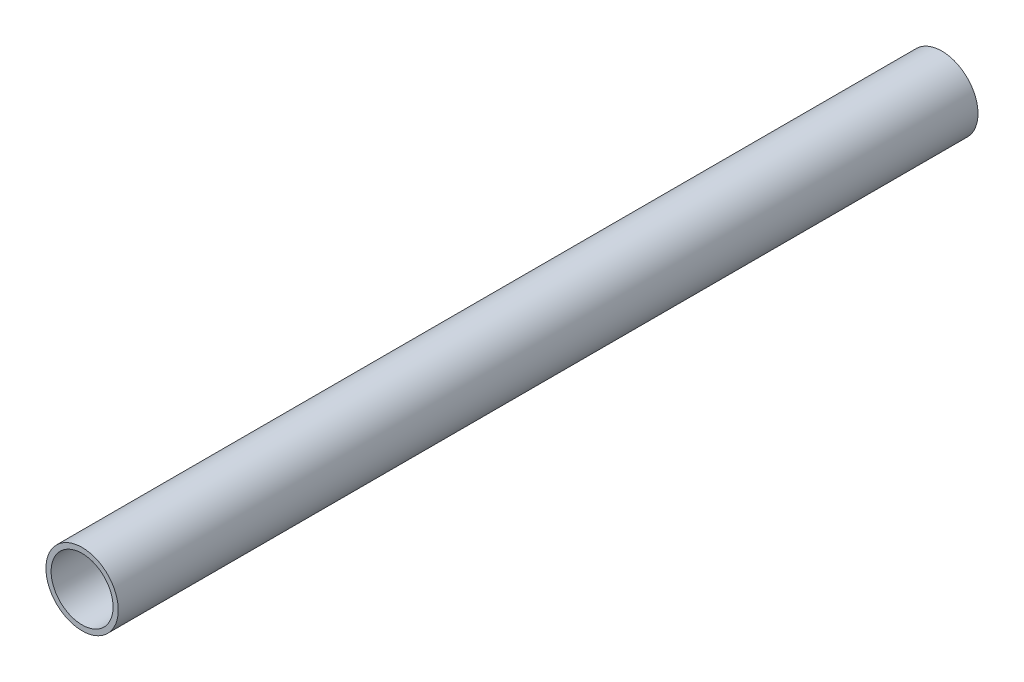
SolidWorks part; units mm, degrees
material "Thornel VCB-20 Carbon Cloth"
ref_plane "Front Plane" through (0, 0, 0) normal (0, 0, 1) x (1, 0, 0)
ref_plane "Top Plane" through (0, 0, 0) normal (0, 1, 0) x (1, 0, 0)
ref_plane "Right Plane" through (0, 0, 0) normal (1, 0, 0) x (0, 0, -1)
sketch "Sketch1" plane through (0, 0, 0) normal (0, 0, 1) x (1, 0, 0)
  circle A0 centre (0, 0) radius 9.525
  circle A1 centre (0, 0) radius 11.1125
  dimension "D1" = 19.05
  dimension "D2" = 22.225
extrude "Boss-Extrude1" add sketch "Sketch1" along normal mid plane 264.2159
